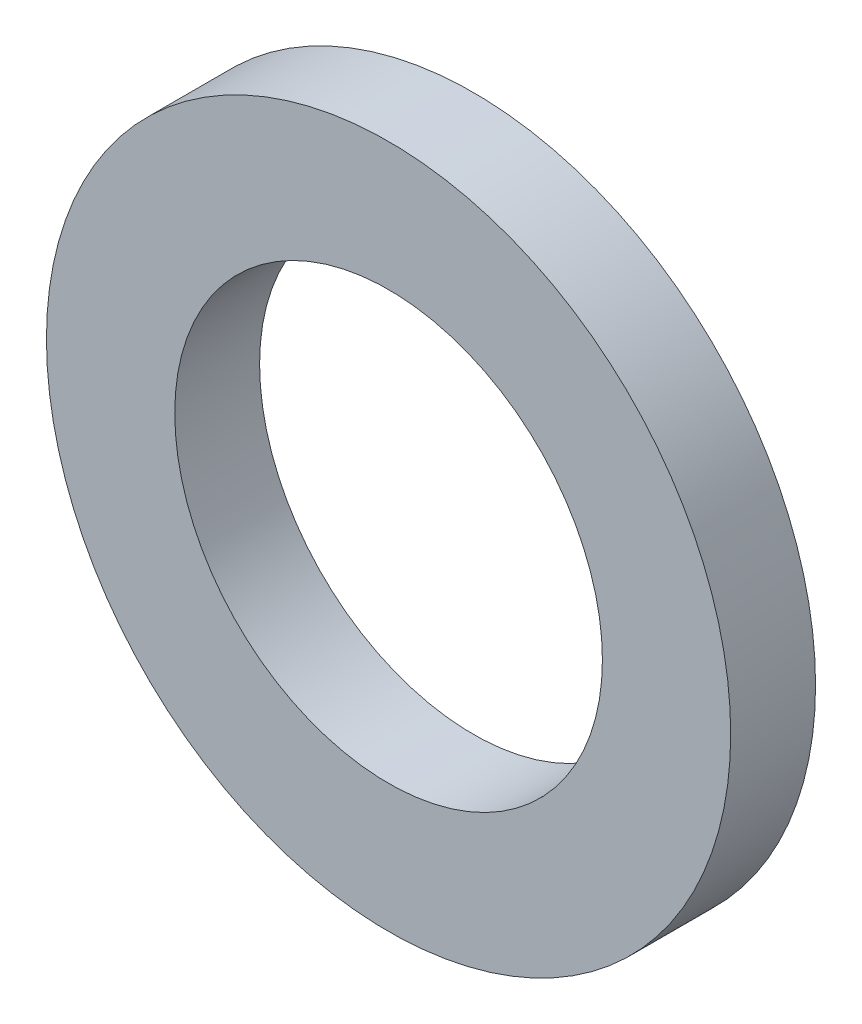
SolidWorks part; units mm, degrees
material "Nylon 6/10"
ref_plane "Front Plane" through (0, 0, 0) normal (0, 0, 1) x (1, 0, 0)
ref_plane "Top Plane" through (0, 0, 0) normal (0, 1, 0) x (1, 0, 0)
ref_plane "Right Plane" through (0, 0, 0) normal (1, 0, 0) x (0, 0, -1)
sketch "Sketch1" plane through (0, 0, 0) normal (0, 0, 1) x (1, 0, 0)
  circle A0 centre (0, 0) radius 6.35
  circle A1 centre (0, 0) radius 3.9688
  dimension "D1" = 12.7
  dimension "D2" = 7.9375
extrude "Extrude1" add sketch "Sketch1" along normal blind 1.5748
